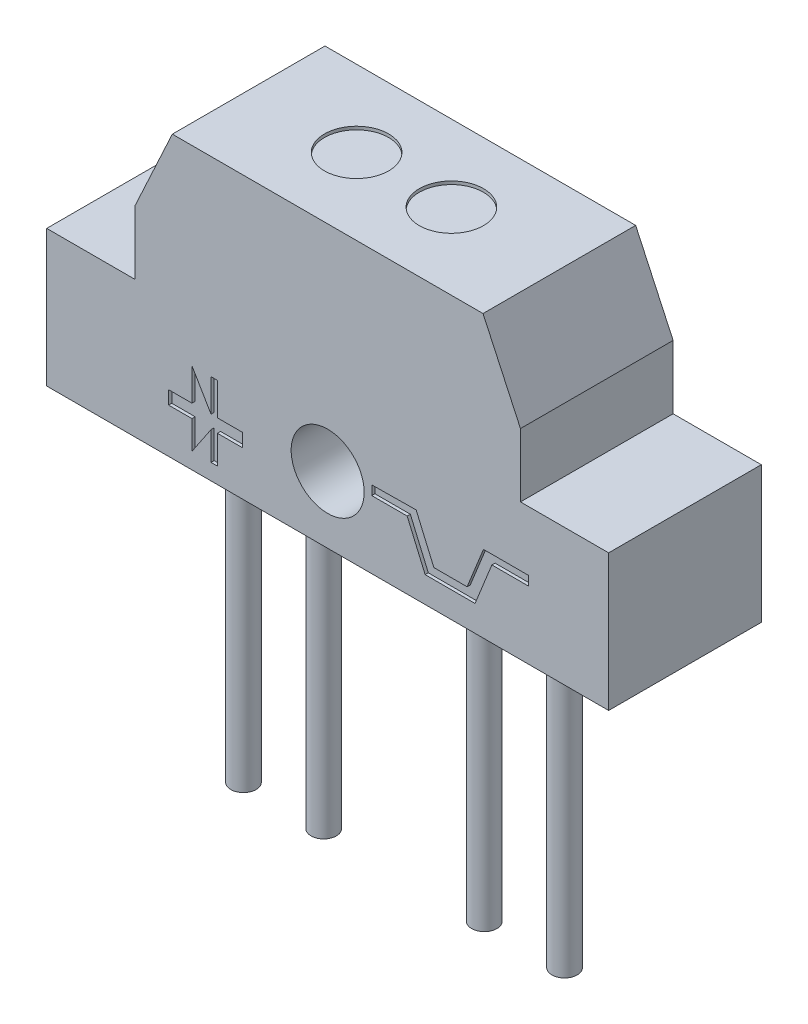
SolidWorks part; units mm, degrees
ref_plane "Спереди" through (0, 0, 0) normal (0, 0, 1) x (1, 0, 0)
ref_plane "Сверху" through (0, 0, 0) normal (0, 1, 0) x (1, 0, 0)
ref_plane "Справа" through (0, 0, 0) normal (1, 0, 0) x (0, 0, -1)
sketch "Эскиз1" plane through (0, 0, 0) normal (0, 1, 0) x (1, 0, 0)
  line L1 (-8.89, 2.415) -> (8.89, 2.415)
  line L2 (-8.89, 2.415) -> (-8.89, -2.415)
  line L3 (-8.89, -2.415) -> (8.89, -2.415)
  line L4 (8.89, 2.415) -> (8.89, -2.415)
  point P4 (0, 2.415)
  point P6 (8.89, 0)
  dimension "D1" = 4.83
  dimension "D2" = 17.78
extrude "Бобышка-Вытянуть1" add sketch "Эскиз1" along normal blind 4.32
sketch "Эскиз2" plane through (0, 4.32, 0) normal (0, 1, 0) x (1, 0, 0)
  line L0 (8.89, 2.415) -> (-8.89, 2.415) construction
  line L1 (-6.1, 2.415) -> (6.1, 2.415)
  line L2 (-6.1, 2.415) -> (-6.1, -2.415)
  line L3 (-6.1, -2.415) -> (6.1, -2.415)
  line L4 (6.1, 2.415) -> (6.1, -2.415)
  line L5 (-8.89, -2.415) -> (8.89, -2.415) construction
  point P8 (0, 2.415)
  dimension "D1" = 12.2
extrude "Бобышка-Вытянуть2" add sketch "Эскиз2" along normal blind 2.01
sketch "Эскиз3" plane through (0, 6.33, 0) normal (0, 1, 0) x (1, 0, 0)
  line L0 (6.1, 2.415) -> (-6.1, 2.415) construction
  line L1 (-4.915, 2.415) -> (4.915, 2.415)
  line L2 (-4.915, 2.415) -> (-4.915, -2.415)
  line L3 (-4.915, -2.415) -> (4.915, -2.415)
  line L4 (4.915, 2.415) -> (4.915, -2.415)
  line L5 (-6.1, -2.415) -> (6.1, -2.415) construction
  point P8 (0, -2.415)
  dimension "D1" = 9.83
extrude "Бобышка-Вытянуть3" add sketch "Эскиз3" along normal blind 2.56
sketch "Эскиз4" plane through (0, 0, 2.415) normal (0, 0, 1) x (1, 0, 0)
  line L0 (-4.915, 8.89) -> (-6.1, 6.33)
  line L1 (-6.1, 6.33) -> (-4.915, 6.33)
  line L2 (-4.915, 6.33) -> (-4.915, 8.89)
  line L3 (4.915, 8.89) -> (4.915, 6.33)
  line L4 (4.915, 6.33) -> (6.1, 6.33)
  line L5 (6.1, 6.33) -> (4.915, 8.89)
extrude "Бобышка-Вытянуть4" add sketch "Эскиз4" against normal up to surface (4.83 mm away) up to face at (0, 5.0317, -2.415)
sketch "Эскиз5" plane through (0, 0, 2.415) normal (0, 0, 1) x (1, 0, 0)
  line L0 (-8.89, 0) -> (8.89, 0) construction
  circle A0 centre (0, 2.11) radius 1.155
  dimension "D2" = 2.31
  dimension "D1" = 2.11
extrude "Вырез-Вытянуть1" cut sketch "Эскиз5" against normal through all
sketch "Эскиз6" plane through (0, 0, 2.415) normal (0, 0, 1) x (1, 0, 0)
  line L0 (-5.0301, 1.829) -> (-5.0301, 1.4067)
  line L1 (-5.0301, 1.4067) -> (-4.2958, 1.4067)
  line L2 (-4.2958, 1.4067) -> (-4.2958, 0.5072)
  line L3 (-4.2958, 0.5072) -> (-3.69, 1.4067)
  line L4 (-3.69, 1.4067) -> (-3.69, 0.5072)
  line L5 (-3.69, 0.5072) -> (-3.488, 0.5072)
  line L6 (-3.488, 0.5072) -> (-3.488, 1.4067)
  line L7 (-3.488, 1.4067) -> (-2.6986, 1.4067)
  line L8 (-2.6986, 1.4067) -> (-2.6986, 1.829)
  line L9 (-2.6986, 1.829) -> (-3.488, 1.829)
  line L10 (-3.488, 1.829) -> (-3.488, 2.857)
  line L11 (-3.488, 2.857) -> (-3.69, 2.857)
  line L12 (-3.69, 2.857) -> (-3.69, 1.829)
  line L13 (-3.69, 1.829) -> (-4.2958, 2.857)
  line L14 (-4.2958, 2.857) -> (-4.2958, 1.829)
  line L15 (-4.2958, 1.829) -> (-5.0301, 1.829)
  line L16 (1.3952, 2.4348) -> (1.3952, 2.1411)
  line L17 (1.3952, 2.1411) -> (2.515, 2.1411)
  line L18 (2.515, 2.1411) -> (3.0841, 0.8193)
  line L19 (3.0841, 0.8193) -> (4.6629, 0.8193)
  line L20 (4.6629, 0.8193) -> (5.1953, 2.1411)
  line L21 (5.1953, 2.1411) -> (6.3519, 2.1411)
  line L22 (6.3519, 2.1411) -> (6.3519, 2.4348)
  line L23 (6.3519, 2.4348) -> (4.9291, 2.4348)
  line L24 (4.9291, 2.4348) -> (4.412, 1.1509)
  line L25 (4.412, 1.1509) -> (3.3595, 1.1509)
  line L26 (3.3595, 1.1509) -> (2.7996, 2.4513)
  line L27 (2.7996, 2.4513) -> (1.3952, 2.4348)
extrude "Вырез-Вытянуть2" cut sketch "Эскиз6" against normal blind 0.1
sketch "Эскиз7" plane through (0, 0, 0) normal (0, -1, 0) x (1, 0, 0)
  line L0 (0, 3.1054) -> (0, -3.1274) construction
  circle A0 centre (5.08, 0) radius 0.4
  circle A1 centre (2.54, 0) radius 0.4
  circle A4 centre (-5.08, 0) radius 0.4
  circle A5 centre (-2.54, 0) radius 0.4
  dimension "D1" = 0.8
  dimension "D2" = 5.08
  dimension "D3" = 2.54
extrude "Бобышка-Вытянуть5" add sketch "Эскиз7" along normal blind 10.16
sketch "Эскиз8" plane through (0, 8.89, 0) normal (0, 1, 0) x (1, 0, 0)
  circle A0 centre (-1.5, 0) radius 1.015
  circle A1 centre (1.5, 0) radius 1.015
  dimension "D1" = 2.03
  dimension "D2" = 1.5
  dimension "D3" = 1.5
extrude "Вырез-Вытянуть3" cut sketch "Эскиз8" against normal blind 0.1
sketch "Эскиз9" plane through (0, 0, -2.415) normal (0, 0, -1) x (-1, 0, 0)
  text T0 "HOA0149-001" font "Arial" height 1
extrude "Вырез-Вытянуть4" cut sketch "Эскиз9" against normal blind 0.1
